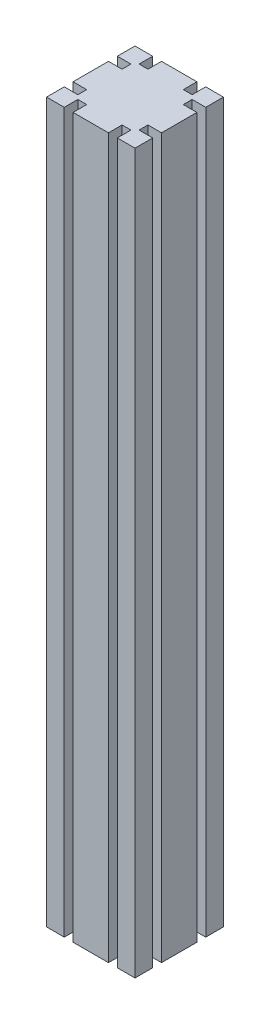
SolidWorks part; units mm, degrees
ref_plane "Front Plane" through (0, 0, 0) normal (0, 0, 1) x (1, 0, 0)
ref_plane "Top Plane" through (0, 0, 0) normal (0, 1, 0) x (1, 0, 0)
ref_plane "Right Plane" through (0, 0, 0) normal (1, 0, 0) x (0, 0, -1)
sketch "Sketch1" plane through (0, 0, 0) normal (0, 1, 0) x (1, 0, 0)
  line L0 (56.6792, 50.48) -> (48.6792, 50.48)
  line L1 (-7.3208, 50.48) -> (8.6792, 50.48)
  line L2 (16.6792, 50.48) -> (48.6792, 50.48)
  line L3 (56.6792, 50.48) -> (72.6792, 50.48)
  line L4 (8.6792, 50.48) -> (16.6792, 50.48)
  line L5 (8.6792, 50.48) -> (8.6792, 38.18)
  line L6 (16.6792, 38.18) -> (8.6792, 38.18)
  line L7 (8.6792, 38.18) -> (8.6792, 50.48)
  line L8 (16.6792, 38.18) -> (16.6792, 50.48)
  line L9 (48.6792, 50.48) -> (48.6792, 38.18)
  line L10 (48.6792, 38.18) -> (56.6792, 38.18)
  line L11 (56.6792, 38.18) -> (56.6792, 50.48)
  line L12 (48.6792, 50.48) -> (48.6792, 38.18)
  line L13 (-7.3208, 50.48) -> (8.6792, 50.48)
  line L14 (72.6792, 50.48) -> (72.6792, 34.48)
  line L15 (72.6792, 34.48) -> (60.3792, 34.48)
  line L17 (60.3792, 34.48) -> (60.3792, 26.48)
  line L19 (60.3792, 26.48) -> (72.6792, 26.48)
  line L21 (72.6792, 26.48) -> (72.6792, -5.52)
  line L22 (72.6792, -5.52) -> (60.3792, -5.52)
  line L23 (60.3792, -5.52) -> (60.3792, -13.52)
  line L24 (60.3792, -13.52) -> (72.6792, -13.52)
  line L28 (72.6792, -13.52) -> (72.6792, -29.52)
  line L29 (72.6792, -29.52) -> (56.6792, -29.52)
  line L30 (56.6792, -29.52) -> (56.6792, -17.22)
  line L31 (56.6792, -17.22) -> (48.6792, -17.22)
  line L32 (48.6792, -17.22) -> (48.6792, -29.52)
  line L33 (48.6792, -29.52) -> (16.6792, -29.52)
  line L34 (16.6792, -29.52) -> (16.6792, -17.22)
  line L35 (16.6792, -17.22) -> (8.6792, -17.22)
  line L36 (8.6792, -17.22) -> (8.6792, -29.52)
  line L37 (8.6792, -29.52) -> (-7.3208, -29.52)
  line L38 (-7.3208, -29.52) -> (-7.3208, -13.52)
  line L39 (-7.3208, -13.52) -> (4.9792, -13.52)
  line L40 (4.9792, -13.52) -> (4.9792, -5.52)
  line L41 (4.9792, -5.52) -> (-7.3208, -5.52)
  line L42 (-7.3208, -5.52) -> (-7.3208, 26.48)
  line L43 (-7.3208, 26.48) -> (4.9792, 26.48)
  line L44 (4.9792, 26.48) -> (4.9792, 34.48)
  line L45 (4.9792, 34.48) -> (-7.3208, 34.48)
  line L46 (-7.3208, 34.48) -> (-7.3208, 50.48)
  point P0 (12.6792, 38.18)
  point P7 (52.6792, 38.18)
  dimension "D1" = 80
  dimension "D2" = 40
  dimension "D3" = 8
  dimension "D4" = 12.3
extrude "Boss-Extrude1" add sketch "Sketch1" along normal blind 650 contours L46 L45 L44 L43 L42 L41 L40 L39 L38 L37 L36 L35 L34 L33 L32 L31 L30 L29 L28 L24 L23 L22 L21 L19 L17 L15 L14 L3 L11 L10 L9 L2 L8 L6 L5 L1
